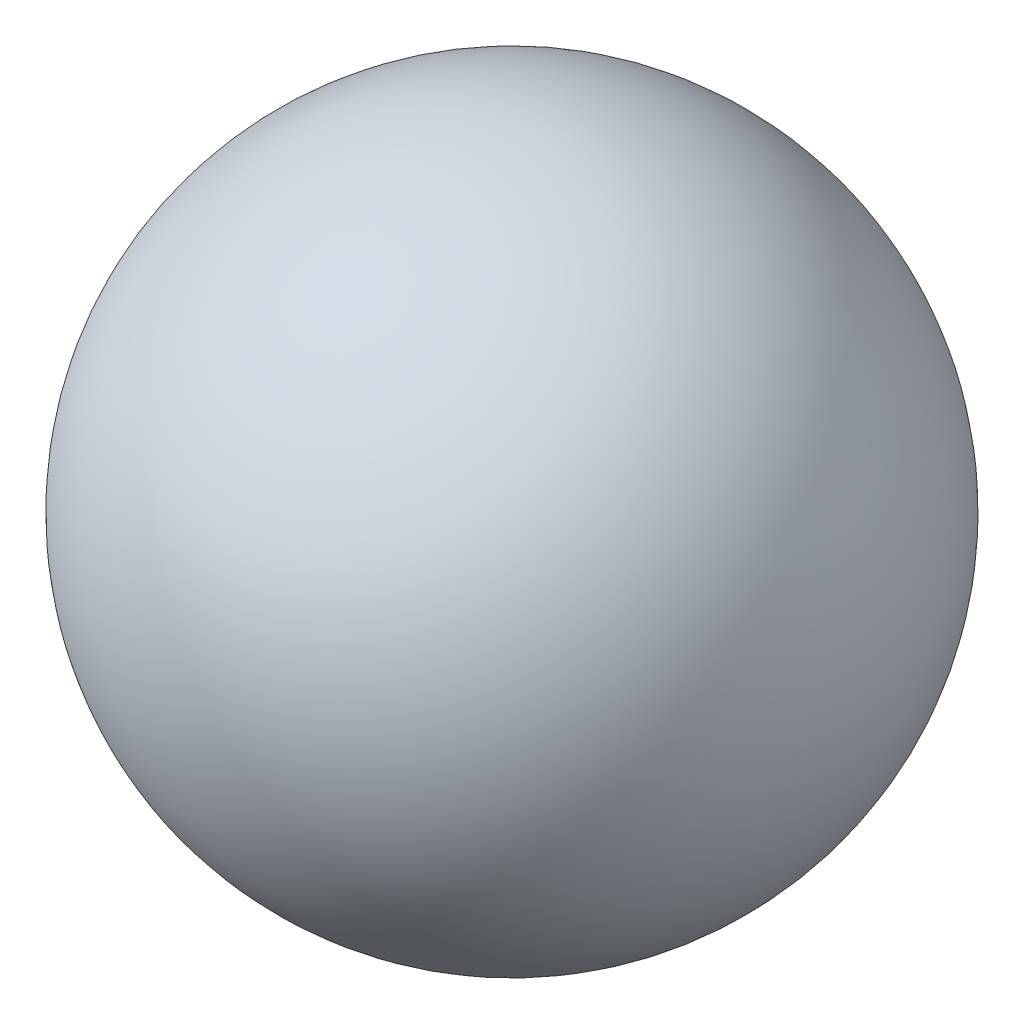
SolidWorks part; units mm, degrees
material "Pine"
ref_plane "Front Plane" through (0, 0, 0) normal (0, 0, 1) x (1, 0, 0)
ref_plane "Top Plane" through (0, 0, 0) normal (0, 1, 0) x (1, 0, 0)
ref_plane "Right Plane" through (0, 0, 0) normal (1, 0, 0) x (0, 0, -1)
sketch "Sketch1" plane through (0, 0, 0) normal (0, 1, 0) x (1, 0, 0)
  line L0 (0, 25.4) -> (0, -25.4)
  arc A0 (0, 25.4) -> (0, -25.4) centre (0, 0) cw
  dimension "D1" = 50.8
revolve "Revolve1" add sketch "Sketch1" angle 360 about L0
